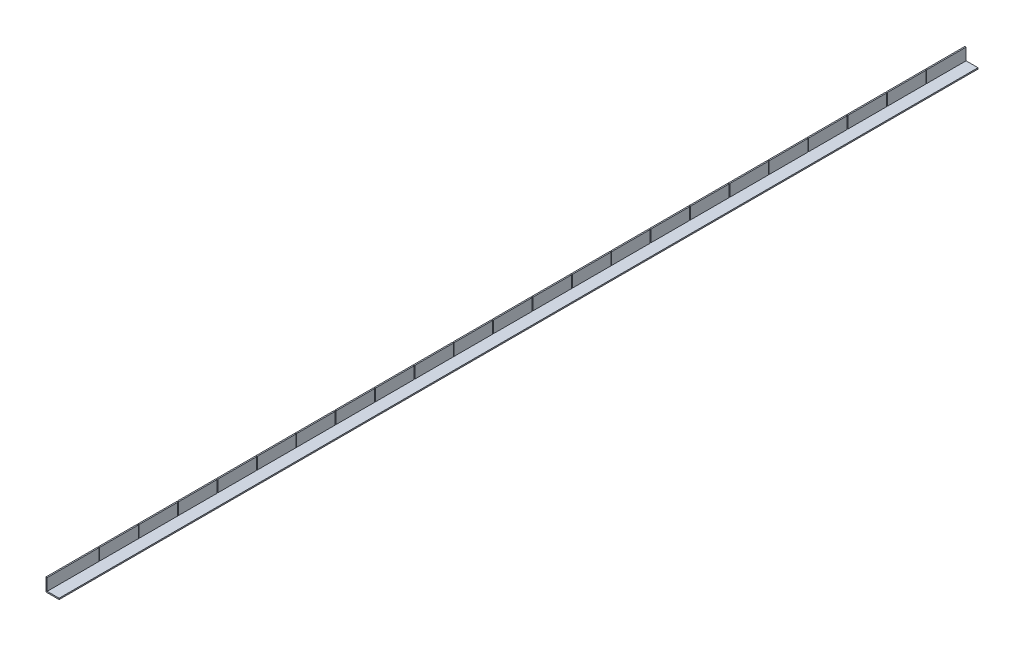
SolidWorks part; units mm, degrees
ref_plane "Front Plane" through (0, 0, 0) normal (0, 0, 1) x (1, 0, 0)
ref_plane "Top Plane" through (0, 0, 0) normal (0, 1, 0) x (1, 0, 0)
ref_plane "Right Plane" through (0, 0, 0) normal (1, 0, 0) x (0, 0, -1)
sketch "Sketch1" plane through (0, 0, 0) normal (0, 0, 1) x (1, 0, 0)
  line L1 (0, 0) -> (50.8, 0)
  line L2 (0, 0) -> (0, 50.8)
  line L3 (0, 50.8) -> (4.7625, 50.8)
  line L4 (50.8, 0) -> (50.8, 4.7625)
  line L7 (50.8, 4.7625) -> (4.7625, 4.7625)
  line L8 (4.7625, 50.8) -> (4.7625, 4.7625)
  dimension "D1" = 50.8
  dimension "D2" = 50.8
  dimension "D3" = 46.0375
  dimension "D4" = 46.0375
extrude "Boss-Extrude1" add sketch "Sketch1" along normal blind 3556
sketch "Sketch2" plane through (4.7625, 0, 0) normal (1, 0, 0) x (0, 0, -1)
  line L0 (-3556, 4.7625) -> (0, 4.7625) construction
  line L1 (-155.575, 4.7625) -> (-152.4, 4.7625)
  line L2 (-155.575, 4.7625) -> (-155.575, 50.8)
  line L3 (-155.575, 50.8) -> (-152.4, 50.8)
  line L4 (-152.4, 4.7625) -> (-152.4, 50.8)
  line L5 (-3556, 50.8) -> (0, 50.8) construction
  dimension "D1" = 3.175
  dimension "D2" = 152.4
extrude "Cut-Extrude1" cut sketch "Sketch2" against normal up to next
pattern_linear "LPattern1" count 22 spacing 152.4 along (0, 0, 1) of "Cut-Extrude1"
